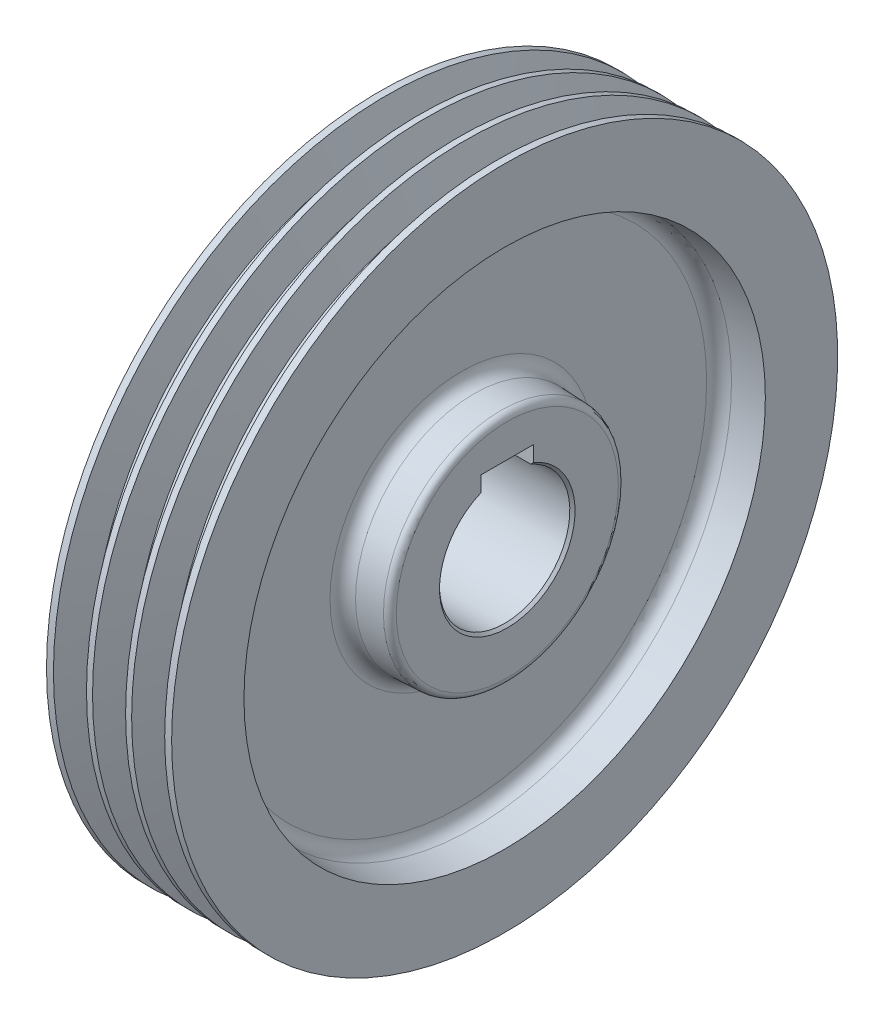
SolidWorks part; units mm, degrees
ref_plane "前视基准面" through (0, 0, 0) normal (0, 0, 1) x (1, 0, 0)
ref_plane "上视基准面" through (0, 0, 0) normal (0, 1, 0) x (1, 0, 0)
ref_plane "右视基准面" through (0, 0, 0) normal (1, 0, 0) x (0, 0, -1)
sketch "草图1" plane through (0, 0, 0) normal (0, 0, 1) x (1, 0, 0)
  line L0 (0, 0) -> (64.8368, 0) construction
  line L1 (-1, 25) -> (-1, 45)
  line L2 (0, 127.75) -> (48, 127.75)
  line L3 (48, 127.75) -> (48, 100)
  line L4 (-1, 45) -> (-30, 45) construction
  line L5 (16.5, 46.5311) -> (16.5, 99.3402)
  line L6 (49, 25) -> (-1, 25)
  line L7 (2.6592, 127.75) -> (6.1599, 116.3) construction
  line L8 (6.1599, 116.3) -> (11.8401, 116.3) construction
  line L9 (11.8401, 116.3) -> (15.3408, 127.75) construction
  line L10 (0, 125) -> (48, 125) construction
  line L11 (9, 116.3) -> (9, 25) construction
  line L12 (44, 100) -> (0, 100) construction
  line L13 (48, 100) -> (79, 100) construction
  line L14 (31.5, 98.5564) -> (31.5, 45.6998)
  line L15 (5, 45) -> (49, 45) construction
  line L16 (24, 25) -> (24, 127.75) construction
  line L17 (49, 45) -> (49, 25)
  line L18 (0, 100) -> (0, 127.75)
  line L19 (16.5, 88) -> (31.5, 88) construction
  line L20 (16.5, 57) -> (31.5, 57) construction
  line L21 (48, 100) -> (48, 88) construction
  line L22 (48, 88) -> (31.5, 88) construction
  line L23 (31.5, 57) -> (49, 57) construction
  line L24 (49, 57) -> (49, 45) construction
  line L25 (31.5, 98.5564) -> (48, 100)
  line L26 (16.5, 99.3402) -> (0, 100)
  line L27 (16.5, 46.5311) -> (-1, 45)
  line L28 (31.5, 45.6998) -> (49, 45)
  point P17 (3.5, 125)
  point P18 (14.5, 125)
  dimension "d2" = 200
  dimension "L" = 50
  dimension "B" = 48
  dimension "d" = 50
  dimension "d1" = 90
  dimension "D3" = 5
  dimension "D4" = 2.29
  dimension "dd" = 250
  dimension "f" = 9
  dimension "槽轮角" = 34
  dimension "bd" = 11
  dimension "hf" = 8.7
  dimension "ha" = 2.75
  dimension "da" = 255.5
  dimension "S" = 15
  dimension "S2" = 12
revolve "旋转1" add sketch "草图1" angle 360 about L0
sketch "草图2" plane through (0, 0, 0) normal (0, 0, 1) x (1, 0, 0)
  line L0 (11.8401, 116.3) -> (15.3408, 127.75) construction
  line L1 (6.1599, 116.3) -> (11.8401, 116.3) construction
  line L2 (2.6592, 127.75) -> (6.1599, 116.3) construction
  line L3 (11.8401, 116.3) -> (15.3408, 127.75)
  line L4 (6.1599, 116.3) -> (11.8401, 116.3)
  line L5 (2.6592, 127.75) -> (6.1599, 116.3)
  line L6 (2.6592, 127.75) -> (15.3408, 127.75)
  line L7 (0, 0) -> (123, 0) construction
revolve "切除-旋转1" cut sketch "草图2" angle 360 about L7
pattern_linear "轮槽数" count 3 spacing 15 along (1, 0, 0) of "切除-旋转1"
chamfer "倒角1" distance 1 2 edges at (-1, 0, 25) (49, 0, 25)
sketch "草图4" plane through (-1, 0, 0) normal (-1, 0, 0) x (0, 0, 1)
  line L1 (-10, 22.9129) -> (10, 22.9129)
  line L2 (-10, 22.9129) -> (-10, 29.9)
  line L3 (-10, 29.9) -> (10, 29.9)
  line L4 (10, 22.9129) -> (10, 29.9)
  circle A0 centre (0, 0) radius 25 construction
  point P6 (5.1, 29.9)
  dimension "键槽高度" = 29.9
  dimension "键槽宽度" = 20
  dimension "t1" = 4.9
extrude "切除-拉伸1" cut sketch "草图4" against normal through all
fillet "圆角1" radius 5 4 edges at (31.5, 0, 98.5564) (16.5, 0, 46.5311) (16.5, 0, 99.3402) (31.5, 0, 45.6998)
fillet "圆角2" radius 2.5 2 edges at (49, 0, 45) (-1, 0, 45)
equation "\"B@草图1\" =  ( \"z@轮槽数\" - 1 )  * \"e@轮槽数\" +2 *  \"f@草图1\""
equation "\"键槽高度@草图4\" = \"d@草图1\" / 2 + \"t1@草图4\""
